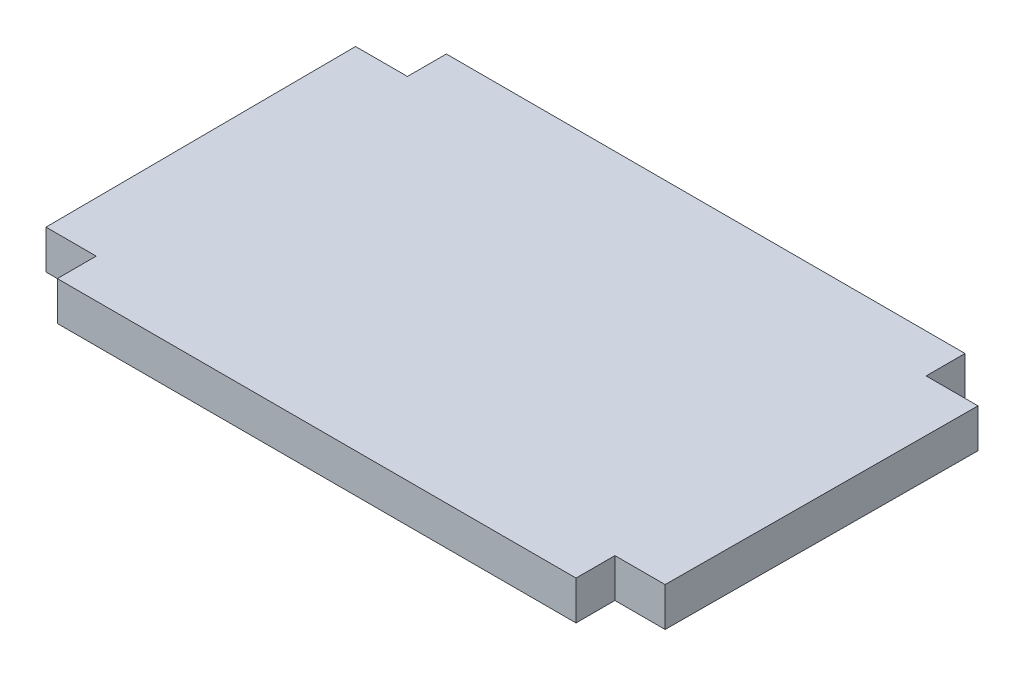
SolidWorks part; units mm, degrees
ref_plane "Alzado" through (0, 0, 0) normal (0, 0, 1) x (1, 0, 0)
ref_plane "Planta" through (0, 0, 0) normal (0, 1, 0) x (1, 0, 0)
ref_plane "Vista lateral" through (0, 0, 0) normal (1, 0, 0) x (0, 0, -1)
sketch "Croquis2" plane through (0, 0, 0) normal (0, 1, 0) x (1, 0, 0)
  line L1 (40, -11.9997) -> (44, -11.9997)
  line L2 (-4, 12) -> (0, 12)
  line L3 (40, 12) -> (40, 15)
  line L4 (40, 15) -> (0, 15)
  line L5 (0, 15) -> (0, 12)
  line L6 (40, 15) -> (40, 12)
  line L7 (0, 12) -> (0, 15)
  line L8 (40, 12) -> (44, 12)
  line L9 (-4, -11.9997) -> (0, -11.9997)
  line L10 (0, -11.9997) -> (0, -14.9997)
  line L11 (-3.8729, -11.9997) -> (-4, 12)
  line L12 (40, -14.9997) -> (40, -11.9997)
  line L13 (0, -14.9997) -> (0, -11.9997)
  line L14 (40, -14.9997) -> (0, -14.9997)
  line L15 (40, -11.9997) -> (40, -14.9997)
  line L19 (43.8729, -11.9997) -> (44, 12)
  dimension "D1" = 40
  dimension "D3" = 4
  dimension "D5" = 4
  dimension "D7" = 24
  dimension "D8" = 24
extrude "Saliente-Extruir1" add sketch "Croquis2" along normal blind 3
